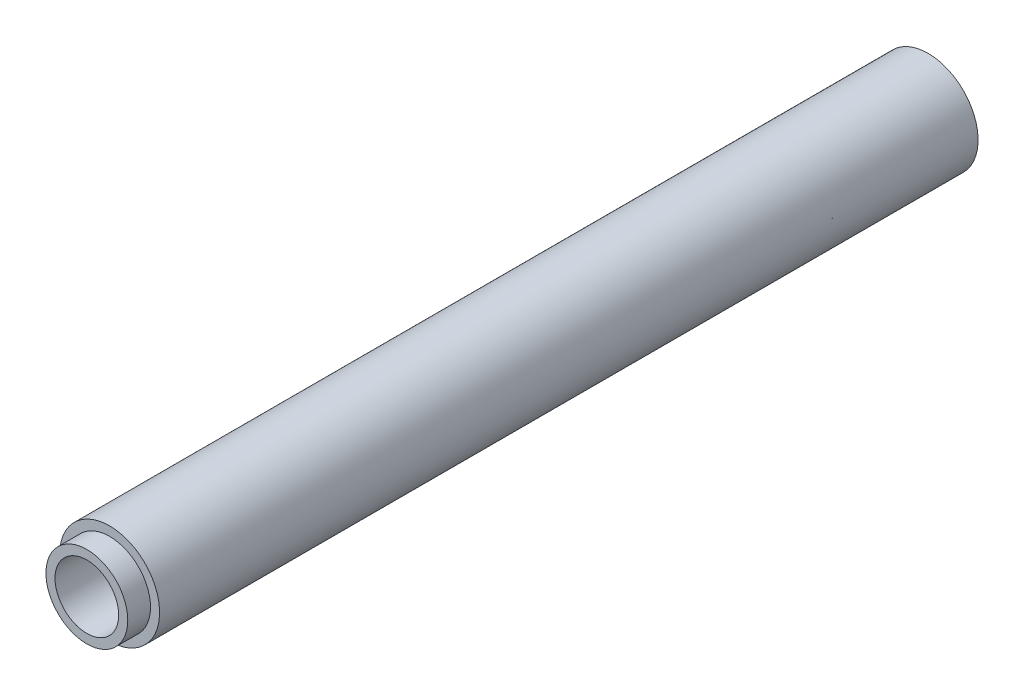
SolidWorks part; units mm, degrees
ref_plane "前视基准面" through (0, 0, 0) normal (0, 0, 1) x (1, 0, 0)
ref_plane "上视基准面" through (0, 0, 0) normal (0, 1, 0) x (1, 0, 0)
ref_plane "右视基准面" through (0, 0, 0) normal (1, 0, 0) x (0, 0, -1)
other "Configuration Table"
sketch "草图1" plane through (0, 0, 0) normal (0, 0, 1) x (1, 0, 0)
  circle A0 centre (0, 0) radius 11
  dimension "D1" = 22
extrude "凸台-拉伸1" add sketch "草图1" along normal blind 180 contours A0
sketch "草图2" plane through (0, 0, 180) normal (0, 0, 1) x (1, 0, 0)
  circle A0 centre (0, 0) radius 9
extrude "凸台-拉伸2" add sketch "草图2" along normal blind 5 contours A0
sketch "草图3" plane through (0, 0, 0) normal (0, 0, -1) x (-1, 0, 0)
  circle A0 centre (0, 0) radius 7
extrude "切除-拉伸1" cut sketch "草图3" against normal through all both and the other way through all
